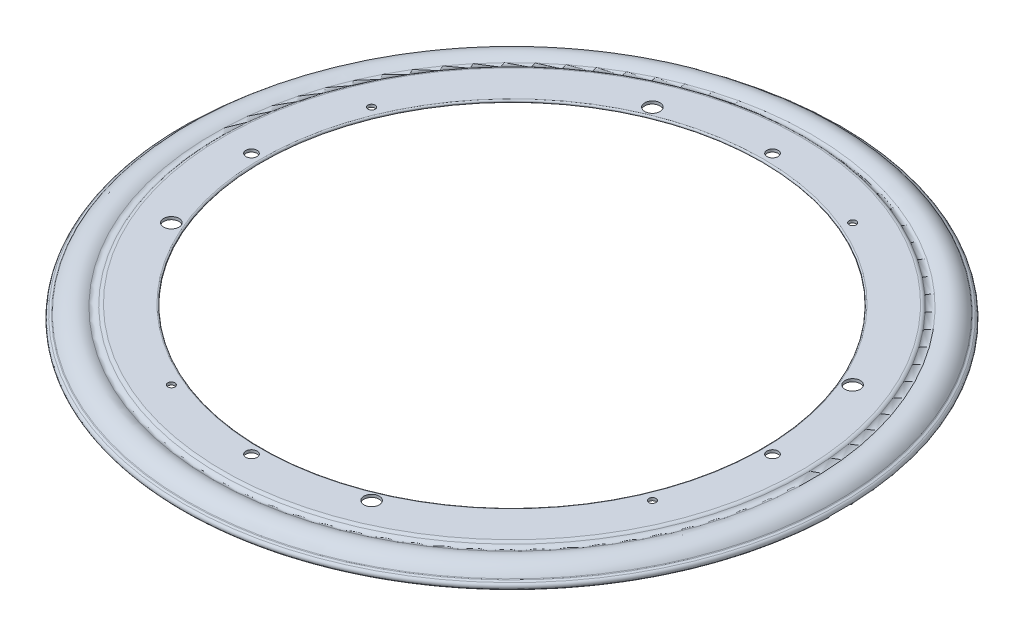
SolidWorks part; units mm, degrees
ref_plane "Front Plane" through (0, 0, 0) normal (0, 0, 1) x (1, 0, 0)
ref_plane "Top Plane" through (0, 0, 0) normal (0, 1, 0) x (1, 0, 0)
ref_plane "Right Plane" through (0, 0, 0) normal (1, 0, 0) x (0, 0, -1)
sketch "Sketch1" plane through (0, 0, 0) normal (1, 0, 0) x (0, 0, -1)
  line L0 (-121.793, 8.89) -> (-116.713, 8.89)
  line L1 (-116.713, 7.62) -> (-121.793, 7.62)
  line L2 (0, 0) -> (0, 8.89) construction
  line L3 (-114.935, 8.89) -> (-116.713, 8.89)
  line L4 (-133.35, 7.62) -> (-121.793, 7.62)
  line L5 (-121.793, 7.62) -> (-121.793, 8.89)
  line L6 (-121.793, 8.89) -> (-132.2484, 8.89)
  line L7 (-149.0638, 4.826) -> (-149.9719, 4.4139)
  line L8 (-133.35, 7.62) -> (-121.793, 7.62)
  line L10 (-121.793, 8.89) -> (-132.2484, 8.89)
  line L11 (-149.0638, 4.826) -> (-149.9719, 4.4139)
  line L12 (-116.713, 8.89) -> (-116.713, 7.62)
  line L13 (-116.713, 7.62) -> (-114.935, 7.62)
  line L14 (-114.935, 8.89) -> (-116.713, 8.89)
  line L16 (-116.713, 7.62) -> (-114.935, 7.62)
  line L17 (0, 8.89) -> (-114.935, 8.89) construction
  arc A1 (-114.935, 7.62) -> (-114.935, 8.89) centre (-114.935, 8.255) ccw
  arc A2 (-114.935, 7.62) -> (-114.935, 8.89) centre (-114.935, 8.255) ccw
  arc A8 (-137.3861, 6.7496) -> (-146.9641, 5.6647) centre (-141.472, 0) ccw
  arc A9 (-137.3861, 6.7496) -> (-133.35, 7.62) centre (-135.8289, 9.3219) ccw
  arc A10 (-132.2484, 8.89) -> (-133.772, 8.1857) centre (-132.2484, 6.89) ccw
  arc A11 (-136.9485, 7.6531) -> (-133.772, 8.1857) centre (-135.6764, 9.8053) ccw
  arc A12 (-136.9485, 7.6531) -> (-148.7789, 5.0638) centre (-141.472, 0) ccw
  arc A13 (-149.0638, 4.826) -> (-148.7789, 5.0638) centre (-149.352, 5.461) ccw
  arc A14 (-149.9719, 4.4139) -> (-147.86, 3.2023) centre (-149.352, 3.048) ccw
  arc A15 (-146.9641, 5.6647) -> (-147.86, 3.2023) centre (-144.8759, 3.5108) ccw
  arc A16 (-137.3861, 6.7496) -> (-146.9641, 5.6647) centre (-141.472, 0) ccw
  arc A17 (-137.3861, 6.7496) -> (-133.35, 7.62) centre (-135.8289, 9.3219) ccw
  arc A18 (-132.2484, 8.89) -> (-133.772, 8.1857) centre (-132.2484, 6.89) ccw
  arc A19 (-136.9485, 7.6531) -> (-133.772, 8.1857) centre (-135.6764, 9.8053) ccw
  arc A20 (-136.9485, 7.6531) -> (-148.7789, 5.0638) centre (-141.472, 0) ccw
  arc A21 (-149.0638, 4.826) -> (-148.7789, 5.0638) centre (-149.352, 5.461) ccw
  arc A22 (-149.9719, 4.4139) -> (-147.86, 3.2023) centre (-149.352, 3.048) ccw
  arc A23 (-146.9641, 5.6647) -> (-147.86, 3.2023) centre (-144.8759, 3.5108) ccw
  dimension "D1" = 0
  dimension "D2" = 0
revolve "Revolve1" add sketch "Sketch1" angle 360 about L2
sketch "Sketch2" plane through (0, 8.89, 0) normal (0, 1, 0) x (1, 0, 0)
  circle A0 centre (-45.8284, -110.0956) radius 1.651 construction
  circle A1 centre (0, -119.253) radius 2.54 construction
  circle A2 centre (45.8284, -110.0956) radius 3.4925 construction
  circle A3 centre (110.0956, -45.8284) radius 1.651 construction
  circle A4 centre (119.253, 0) radius 2.54 construction
  circle A5 centre (110.0956, 45.8284) radius 3.4925 construction
  circle A6 centre (45.8284, 110.0956) radius 1.651 construction
  circle A7 centre (-110.0956, -45.8284) radius 3.4925 construction
  circle A8 centre (-119.253, 0) radius 2.54 construction
  circle A9 centre (-110.0956, 45.8284) radius 1.651 construction
  circle A10 centre (0, 119.253) radius 2.54 construction
  circle A11 centre (-45.8284, 110.0956) radius 3.4925 construction
  circle A12 centre (-45.8284, -110.0956) radius 1.651
  circle A13 centre (0, -119.253) radius 2.54
  circle A14 centre (45.8284, -110.0956) radius 3.4925
  circle A15 centre (110.0956, -45.8284) radius 1.651
  circle A16 centre (119.253, 0) radius 2.54
  circle A17 centre (110.0956, 45.8284) radius 3.4925
  circle A18 centre (45.8284, 110.0956) radius 1.651
  circle A19 centre (-110.0956, -45.8284) radius 3.4925
  circle A20 centre (-119.253, 0) radius 2.54
  circle A21 centre (-110.0956, 45.8284) radius 1.651
  circle A22 centre (0, 119.253) radius 2.54
  circle A23 centre (-45.8284, 110.0956) radius 3.4925
extrude "Cut-Extrude1" cut sketch "Sketch2" against normal up to surface (1.27 mm away) up to face at (0, 7.62, -114.935)
